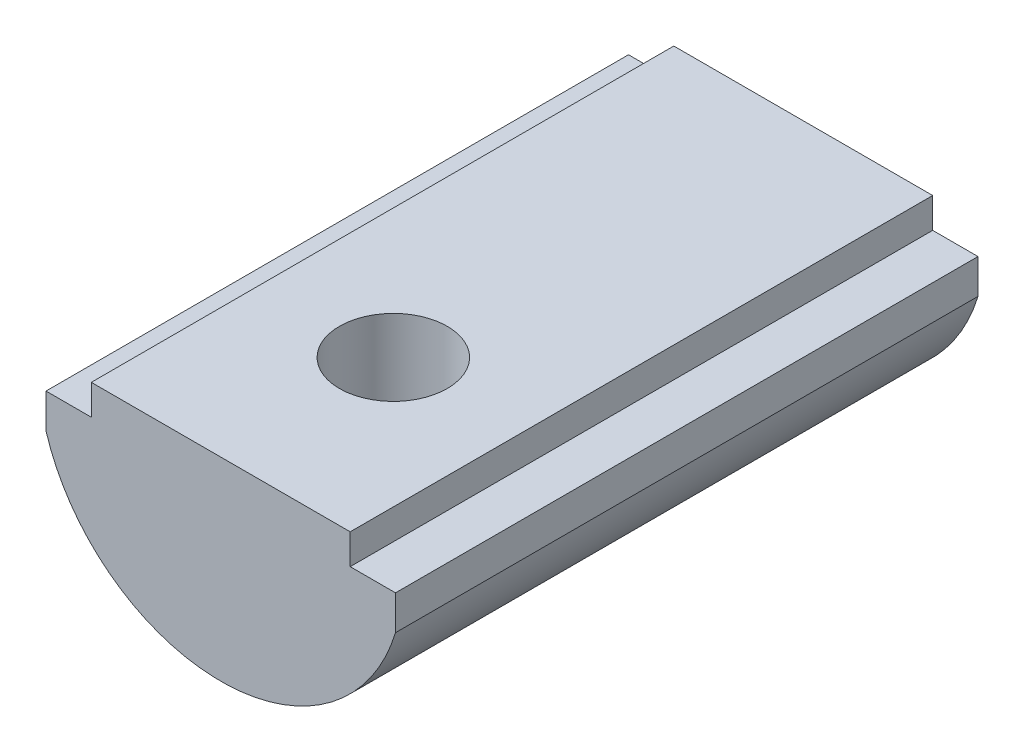
SolidWorks part; units mm, degrees
ref_plane "Plan de face" through (0, 0, 0) normal (0, 0, 1) x (1, 0, 0)
ref_plane "Plan de dessus" through (0, 0, 0) normal (0, 1, 0) x (1, 0, 0)
ref_plane "Plan de droite" through (0, 0, 0) normal (1, 0, 0) x (0, 0, -1)
sketch "Esquisse1" plane through (0, 0, 0) normal (0, 0, 1) x (1, 0, 0)
  line L0 (-3, 0) -> (3, 0)
  line L1 (3, 0) -> (3, -0.7)
  line L2 (3, -0.7) -> (4.05, -0.7)
  line L3 (4.05, -0.7) -> (4.05, -1.5)
  line L4 (0, 0) -> (0, -4.5) construction
  line L5 (-4.05, -0.7) -> (-4.05, -1.5)
  line L6 (-3, -0.7) -> (-4.05, -0.7)
  line L7 (-3, 0) -> (-3, -0.7)
  arc A0 (4.05, -1.5) -> (-4.05, -1.5) centre (0, -0.2662) cw
  dimension "D1" = 8.1
  dimension "D2" = 6
  dimension "D3" = 0.7
  dimension "D4" = 4.5
  dimension "D5" = 0.8
extrude "Boss.-Extru.1" add sketch "Esquisse1" along normal blind 13.5
hole_wizard "Trou pour taraudage pour trou taraudé M31" positions "Esquisse2" profile "Esquisse3" hole size "M3" standard "DIN" end condition through all
sketch "Esquisse2" plane through (0, 0, 0) normal (0, 1, 0) x (1, 0, 0)
  line L0 (3, -13.5) -> (-3, -13.5) construction
  point P0 (0, -9.5)
  dimension "D1" = 4
sketch "Esquisse3" plane through (0, 0, 9.5) normal (1, 0, 0) x (0, 0, 1)
  line L0 (0, 0) -> (0, 4.5)
  line L1 (0, 4.5) -> (1.25, 4.5)
  line L2 (1.25, 4.5) -> (1.25, 0)
  line L5 (1.25, 0) -> (0, 0)
  line L11 (0, -6.35) -> (0, 107.95) construction
  dimension "Diamètre du perçage jusqu'au prochain" = 2.5
  dimension "Profondeur du perçage jusqu'au prochain" = 4.5
sketch "Esquisse4" plane through (0, 0, 0) normal (1, 0, 0) x (0, 0, -1)
  line L1 (0, -4.5) -> (0, -1.5) construction
  line L2 (-3, -3.3) -> (-3, -5.3)
  line L3 (-8.25, -4.5) -> (0, -4.5) construction
  arc A0 (-3, -5.3) -> (-3, -3.3) centre (-3, -4.3) ccw
  point P1 (0, 0)
  dimension "D1" = 2
  dimension "D2" = 3
  dimension "D3" = 0.8
revolve "Révolution1" add sketch "Esquisse4" angle 360 about L2
